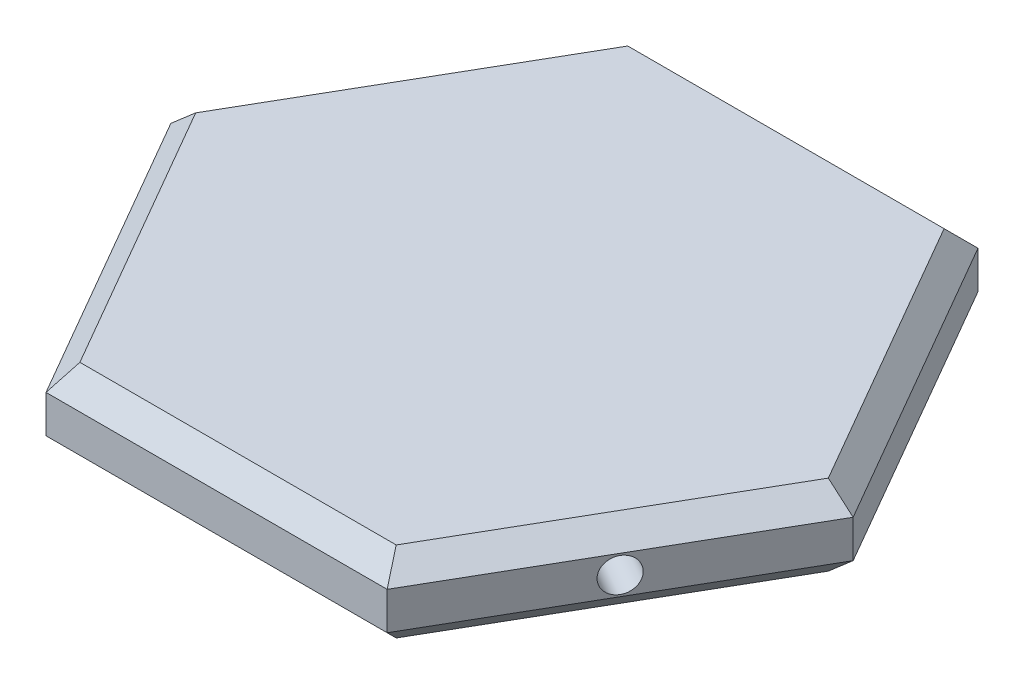
SolidWorks part; units mm, degrees
ref_plane "Front Plane" through (0, 0, 0) normal (0, 0, 1) x (1, 0, 0)
ref_plane "Top Plane" through (0, 0, 0) normal (0, 1, 0) x (1, 0, 0)
ref_plane "Right Plane" through (0, 0, 0) normal (1, 0, 0) x (0, 0, -1)
sketch "Sketch1" plane through (0, 0, 0) normal (0, 1, 0) x (1, 0, 0)
  line L0 (-17.6954, 0) -> (21.2766, 0) construction
  line L1 (40.3279, -69.85) -> (80.6558, 0)
  line L2 (80.6558, 0) -> (40.3279, 69.85)
  line L3 (40.3279, 69.85) -> (-40.3279, 69.85)
  line L4 (-40.3279, 69.85) -> (-80.6558, 0)
  line L5 (-80.6558, 0) -> (-40.3279, -69.85)
  line L6 (-40.3279, -69.85) -> (40.3279, -69.85)
  circle A0 centre (0, 0) radius 69.85 construction
  dimension "D1" = 139.7
extrude "Boss-Extrude1" add sketch "Sketch1" along normal blind 19.05
chamfer "Chamfer1" distance 5.08 angle 45 12 edges at (-60.4919, 0, 34.925) (-60.4919, 0, -34.925) (0, 0, -69.85) (60.4919, 0, -34.925) (60.4919, 0, 34.925) (0, 0, 69.85) (-60.4919, 19.05, 34.925) (-60.4919, 19.05, -34.925) (0, 19.05, -69.85) (60.4919, 19.05, -34.925) (60.4919, 19.05, 34.925) (0, 19.05, 69.85)
sketch "Sketch2" plane through (-60.4919, 0, 34.925) normal (-0.866, 0, 0.5) x (0.5, 0, 0.866)
  line L0 (40.3279, 13.97) -> (-40.3279, 13.97) construction
  line L1 (-40.3279, 13.97) -> (-40.3279, 5.08) construction
  circle A0 centre (0, 9.525) radius 4
  point P4 (0, 13.97)
  point P5 (0, 0)
  point P8 (-40.3279, 9.525)
  dimension "D1" = 8
extrude "Cut-Extrude1" cut sketch "Sketch2" against normal blind 12.7 contours A0
pattern_circular "CirPattern1" count 3 over 360 about axis through (0, 0, 0) along (0, 1, 0) of "Cut-Extrude1"
